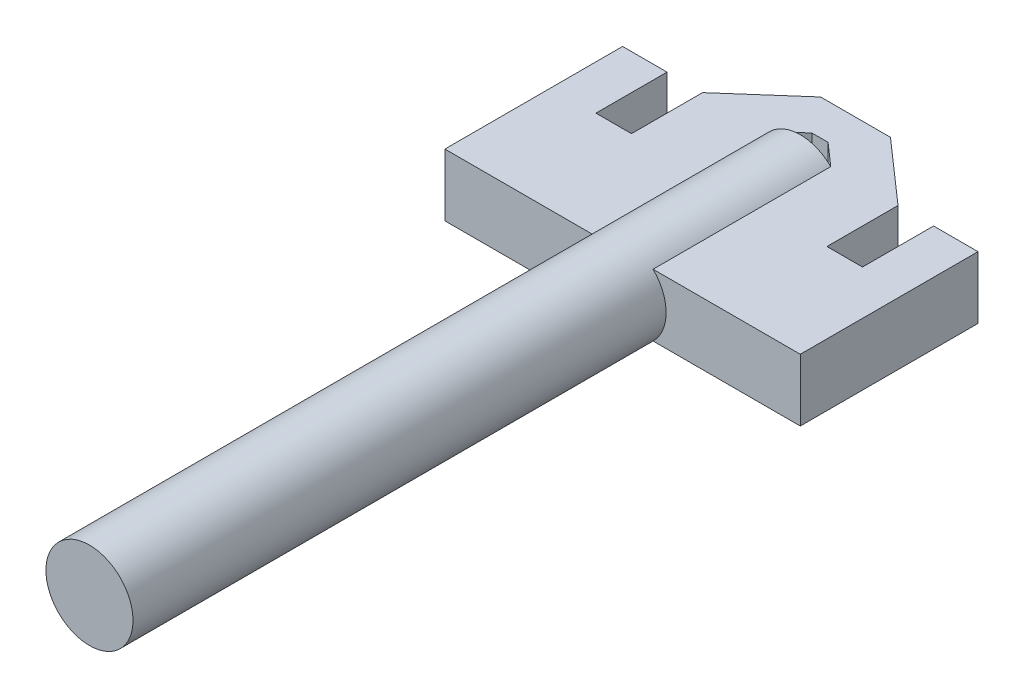
SolidWorks part; units mm, degrees
ref_plane "Front Plane" through (0, 0, 0) normal (0, 0, 1) x (1, 0, 0)
ref_plane "Top Plane" through (0, 0, 0) normal (0, 1, 0) x (1, 0, 0)
ref_plane "Right Plane" through (0, 0, 0) normal (1, 0, 0) x (0, 0, -1)
sketch "Sketch2" plane through (0, 0, 0) normal (0, 0, 1) x (1, 0, 0)
  circle A0 centre (0, 0) radius 2.45
  dimension "D1" = 4.9
extrude "Boss-Extrude1" add sketch "Sketch2" along normal blind 40
sketch "Sketch3" plane through (0, 0, 0) normal (0, 0, -1) x (-1, 0, 0)
  line L0 (-10, 1.75) -> (10, 1.75)
  line L1 (10, 1.75) -> (10, -1.75)
  line L4 (-10, 1.75) -> (-10, -1.75)
  line L5 (-10, -1.75) -> (10, -1.75)
  circle A1 centre (0, 0) radius 2.45 construction
  point P3 (10, 0)
  point P5 (0, 1.75)
  dimension "D1" = 1.75
  dimension "D4" = 20
extrude "Boss-Extrude2" add sketch "Sketch3" against normal blind 10
sketch "Sketch4" plane through (0, 0, 0) normal (0, 0, -1) x (-1, 0, 0)
  line L0 (0, 2.45) -> (0, -2.45) construction
  line L1 (-10, -1.75) -> (-1.7146, -1.75) construction
  line L2 (-7.5, 1.75) -> (-5.5, 1.75)
  line L3 (-7.5, 1.75) -> (-7.5, -1.75)
  line L4 (-7.5, -1.75) -> (-5.5, -1.75)
  line L5 (-5.5, 1.75) -> (-5.5, -1.75)
  line L6 (-7.5, 1.75) -> (-5.5, -1.75) construction
  line L7 (-7.5, -1.75) -> (-5.5, 1.75) construction
  line L8 (-1.7146, 1.75) -> (-10, 1.75) construction
  line L9 (-10, 1.75) -> (-10, -1.75) construction
  line L10 (7.5, -1.75) -> (5.5, 1.75) construction
  line L11 (7.5, 1.75) -> (5.5, -1.75) construction
  line L12 (5.5, 1.75) -> (5.5, -1.75)
  line L13 (7.5, -1.75) -> (5.5, -1.75)
  line L14 (7.5, 1.75) -> (7.5, -1.75)
  line L15 (7.5, 1.75) -> (5.5, 1.75)
  point P5 (0, 0)
  point P8 (-6.5, 0)
  point P23 (6.5, 0)
  point P24 (0, 0)
  dimension "D1" = 2.5
  dimension "D2" = 2
extrude "Cut-Extrude1" cut sketch "Sketch4" against normal blind 4
sketch "Sketch5" plane through (0, 0, 0) normal (0, 1, 0) x (1, 0, 0)
  line L0 (-1.7146, 0) -> (-0.4535, 1.1092)
  line L2 (-0.4535, 1.1092) -> (0.4535, 1.1092)
  line L3 (0.4535, 1.1092) -> (1.7146, 0)
  line L5 (-1.7146, 0) -> (-5.5, 0)
  line L6 (-5.5, 0) -> (-1.965, 3.1092)
  line L7 (-1.965, 3.1092) -> (1.965, 3.1092)
  line L8 (1.965, 3.1092) -> (5.5, 0)
  line L9 (1.7146, 0) -> (5.5, 0)
  point P2 (0, 0)
  point P3 (0, 0)
  point P4 (0, 0)
  dimension "D2" = 2
  dimension "D3" = 2.5
extrude "Boss-Extrude3" add sketch "Sketch5" along normal up to surface and the other way up to surface
